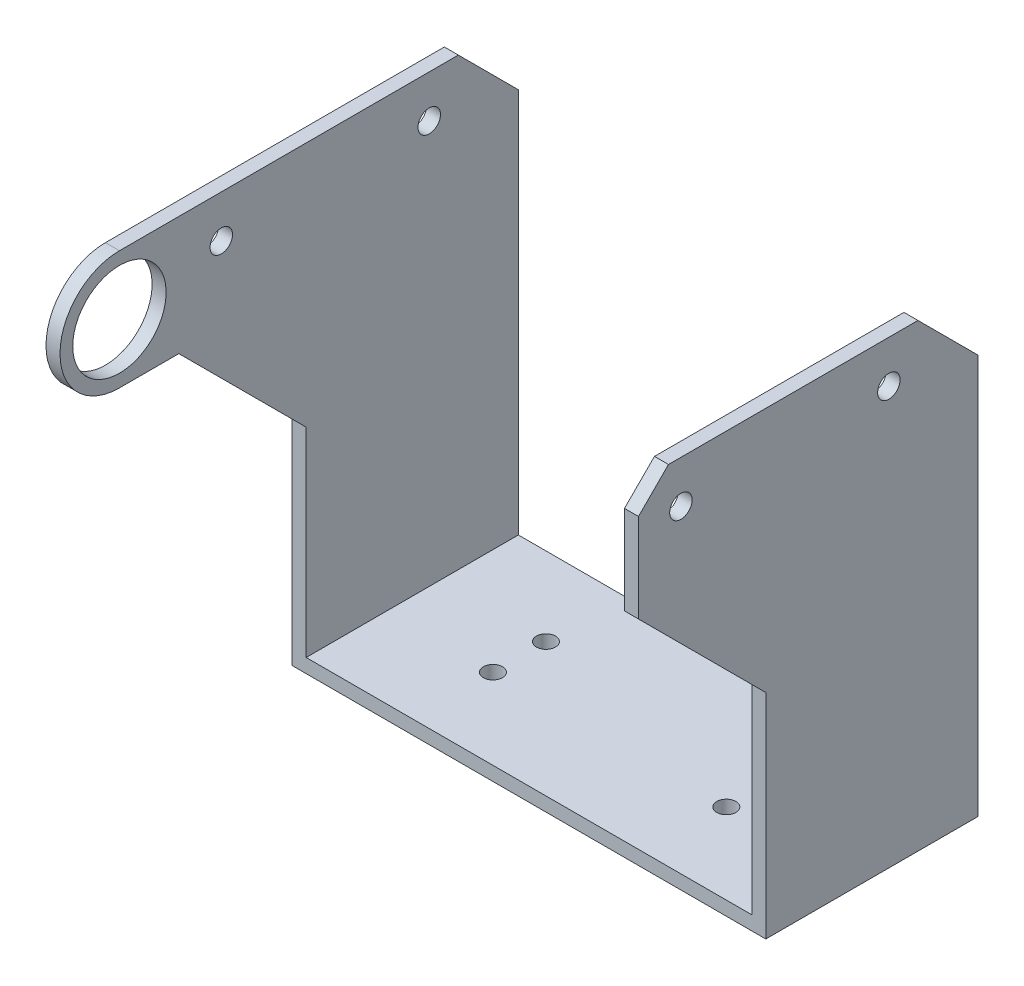
SolidWorks part; units mm, degrees
material "1060 Alloy"
ref_plane "Front Plane" through (0, 0, 0) normal (0, 0, 1) x (1, 0, 0)
ref_plane "Top Plane" through (0, 0, 0) normal (0, 1, 0) x (1, 0, 0)
ref_plane "Right Plane" through (0, 0, 0) normal (1, 0, 0) x (0, 0, -1)
sketch "Sketch1" plane through (0, 0, 0) normal (0, 1, 0) x (1, 0, 0)
  line L0 (0, -55) -> (0, 55) construction
  line L1 (-52.5, -25) -> (52.5, -25)
  line L2 (-52.5, -25) -> (-52.5, 25)
  line L3 (-52.5, 25) -> (52.5, 25)
  line L4 (52.5, -25) -> (52.5, 25)
  line L5 (-52.5, -25) -> (52.5, 25) construction
  line L6 (-52.5, 25) -> (52.5, -25) construction
  circle A0 centre (-27.5, 6.5) radius 2.25
  circle A1 centre (-27.5, -6) radius 2.25
  circle A4 centre (27.5, -6) radius 2.25
  circle A5 centre (27.5, 6.5) radius 2.25
  point P0 (0, 0)
  dimension "D4" = 4.5
  dimension "D1" = 105
  dimension "D2" = 50
  dimension "D3" = 12.5
  dimension "D5" = 27.5
  dimension "D6" = 19
extrude "Boss-Extrude1" add sketch "Sketch1" along normal blind 3.3
sketch "Sketch2" plane through (52.5, 0, 0) normal (1, 0, 0) x (0, 0, -1)
  line L0 (25, 0) -> (25, 94.1579)
  line L1 (25, 94.1579) -> (10.8579, 108.3)
  line L2 (10.8579, 108.3) -> (-47.9289, 108.3)
  line L3 (-47.9289, 108.3) -> (-55, 101.2289)
  line L4 (-55, 101.2289) -> (-55, 80.3)
  line L5 (-55, 80.3) -> (-25, 50.3)
  line L6 (-25, 50.3) -> (-25, 0)
  line L7 (-25, 0) -> (25, 0)
  line L8 (-25, 3.3) -> (25, 3.3) construction
  circle A0 centre (-45, 98.3) radius 2.65
  circle A1 centre (4, 98.3) radius 2.65
  dimension "D7" = 5.3
  dimension "D1" = 135
  dimension "D2" = 20
  dimension "D3" = 10
  dimension "D4" = 80
  dimension "D5" = 105
  dimension "D6" = 58
  dimension "D8" = 49
  dimension "D9" = 10
  dimension "D10" = 10
extrude "Boss-Extrude2" add sketch "Sketch2" along normal blind 3.3
sketch "Sketch3" plane through (-52.5, 0, 0) normal (-1, 0, 0) x (0, 0, 1)
  line L0 (47.9289, 108.3) -> (69, 108.3)
  line L1 (55, 80.3) -> (69, 80.3)
  line L8 (-25, 0) -> (25, 0)
  line L9 (-25, 94.1579) -> (-25, 0)
  line L10 (-10.8579, 108.3) -> (-25, 94.1579)
  line L11 (47.9289, 108.3) -> (-10.8579, 108.3)
  line L12 (55, 101.2289) -> (47.9289, 108.3)
  line L13 (55, 80.3) -> (55, 101.2289)
  line L14 (25, 50.3) -> (55, 80.3)
  line L15 (25, 0) -> (25, 50.3)
  line L16 (-25, 0) -> (25, 0)
  line L17 (-25, 94.1579) -> (-25, 0)
  line L18 (-10.8579, 108.3) -> (-25, 94.1579)
  line L19 (47.9289, 108.3) -> (-10.8579, 108.3)
  line L22 (25, 50.3) -> (55, 80.3)
  line L23 (25, 0) -> (25, 50.3)
  arc A0 (69, 80.3) -> (69, 108.3) centre (69, 94.3) ccw
  circle A1 centre (69, 94.3) radius 11
  circle A2 centre (-4, 98.3) radius 2.65 construction
  circle A3 centre (45, 98.3) radius 2.65 construction
  circle A4 centre (-4, 98.3) radius 2.65
  circle A5 centre (45, 98.3) radius 2.65
  dimension "D2" = 28
  dimension "D3" = 94
  dimension "D4" = 3
  dimension "D1" = 0
extrude "Boss-Extrude3" add sketch "Sketch3" along normal blind 3.3
